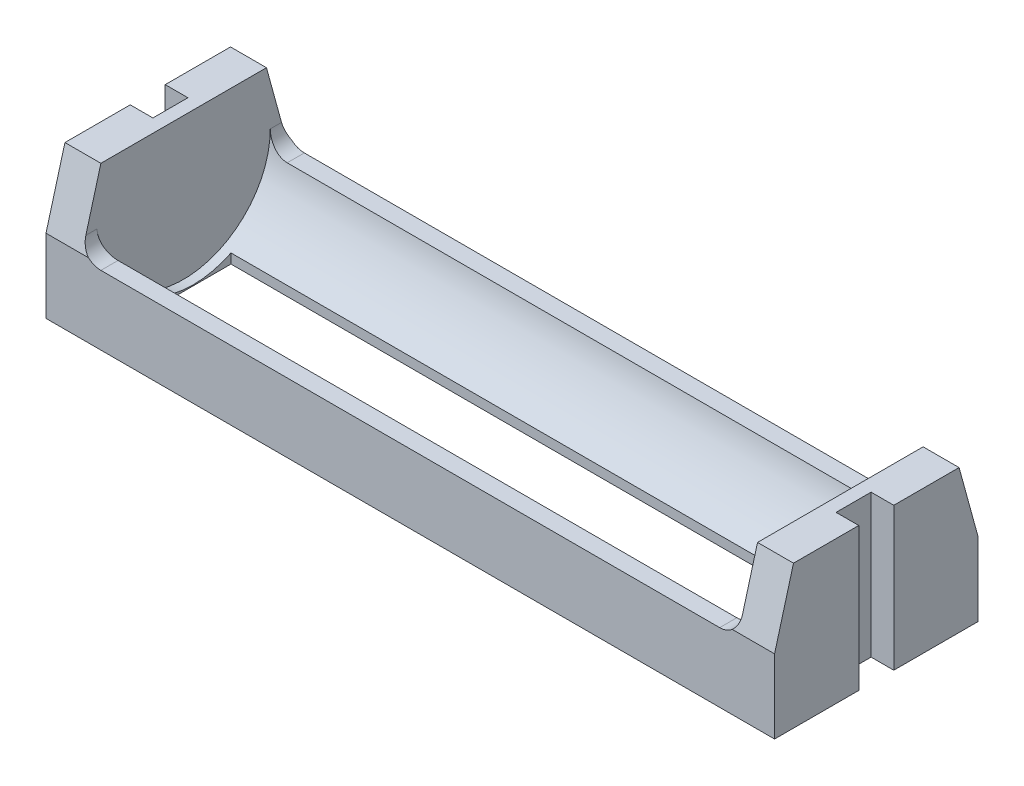
SolidWorks part; units mm, degrees
material "PF"
ref_plane "Спереди" through (0, 0, 0) normal (0, 0, 1) x (1, 0, 0)
ref_plane "Сверху" through (0, 0, 0) normal (0, 1, 0) x (1, 0, 0)
ref_plane "Справа" through (0, 0, 0) normal (1, 0, 0) x (0, 0, -1)
sketch "Эскиз1" plane through (0, 0, 0) normal (0, 1, 0) x (1, 0, 0)
  line L1 (-38.5, 10.75) -> (38.5, 10.75)
  line L2 (-38.5, 10.75) -> (-38.5, -10.75)
  line L3 (-38.5, -10.75) -> (38.5, -10.75)
  line L4 (38.5, 10.75) -> (38.5, -10.75)
  line L5 (-38.5, 10.75) -> (38.5, -10.75) construction
  line L6 (-38.5, -10.75) -> (38.5, 10.75) construction
  point P0 (0, 0)
  dimension "D1" = 77
  dimension "D2" = 21.5
extrude "Бобышка-Вытянуть1" add sketch "Эскиз1" along normal blind 15.1
chamfer "Фаска1" distance 7.3 distance2 2 2 edges at (0, 15.1, -10.75) (0, 15.1, 10.75)
sketch "Эскиз2" plane through (0, 0, 10.75) normal (0, 0, 1) x (1, 0, 0)
  line L0 (-38.5, 15.1) -> (38.5, 15.1) construction
  line L1 (-34.7, 15.1) -> (34.7, 15.1)
  line L2 (-34.7, 15.1) -> (-34.7, 9.3)
  line L3 (-32.7, 7.3) -> (32.7, 7.3)
  line L4 (34.7, 15.1) -> (34.7, 9.3)
  line L5 (38.5, 7.8) -> (38.5, 0) construction
  arc A0 (32.7, 7.3) -> (34.7, 9.3) centre (32.7, 9.3) ccw
  arc A1 (-32.7, 7.3) -> (-34.7, 9.3) centre (-32.7, 9.3) cw
  point P6 (0, 7.3)
  dimension "D3" = 2
  dimension "D1" = 7.3
  dimension "D2" = 3.8
extrude "Вырез-Вытянуть1" cut sketch "Эскиз2" against normal through all
sketch "Эскиз3" plane through (38.5, 0, 0) normal (1, 0, 0) x (0, 0, -1)
  circle A0 centre (0, 9.25) radius 9.15
  dimension "D1" = 18.3
  dimension "D2" = 9.25
extrude "Вырез-Вытянуть2" cut sketch "Эскиз3" against normal up to surface (69.4 mm away) from surface at -3.8 up to face at (-34.7, 12.2, 0) starting at face at (34.7, 12.2, 0)
sketch "Эскиз4" plane through (0, 0, 0) normal (0, -1, 0) x (1, 0, 0)
  line L0 (34.7, 9.15) -> (34.7, -9.15) construction
  line L1 (-33.7, 4) -> (33.7, 4)
  line L2 (-33.7, 4) -> (-33.7, -4)
  line L3 (-33.7, -4) -> (33.7, -4)
  line L4 (33.7, 4) -> (33.7, -4)
  line L5 (-33.7, 4) -> (33.7, -4) construction
  line L6 (-33.7, -4) -> (33.7, 4) construction
  line L7 (-38.5, -10.75) -> (-38.5, 10.75) construction
  line L8 (-38.5, 1.85) -> (-36.1, 1.85)
  line L9 (-38.5, 1.85) -> (-38.5, -1.85)
  line L10 (-38.5, -1.85) -> (-36.1, -1.85)
  line L11 (-36.1, 1.85) -> (-36.1, -1.85)
  line L12 (38.5, 10.75) -> (38.5, -10.75) construction
  line L13 (38.5, 1.85) -> (36.1, 1.85)
  line L14 (38.5, 1.85) -> (38.5, -1.85)
  line L15 (38.5, -1.85) -> (36.1, -1.85)
  line L16 (36.1, 1.85) -> (36.1, -1.85)
  point P0 (0, 0)
  point P20 (-36.1, 0)
  point P21 (36.1, 0)
  dimension "D1" = 1
  dimension "D2" = 8
  dimension "D3" = 3.7
  dimension "D4" = 2.4
extrude "Вырез-Вытянуть3" cut sketch "Эскиз4" against normal through all
